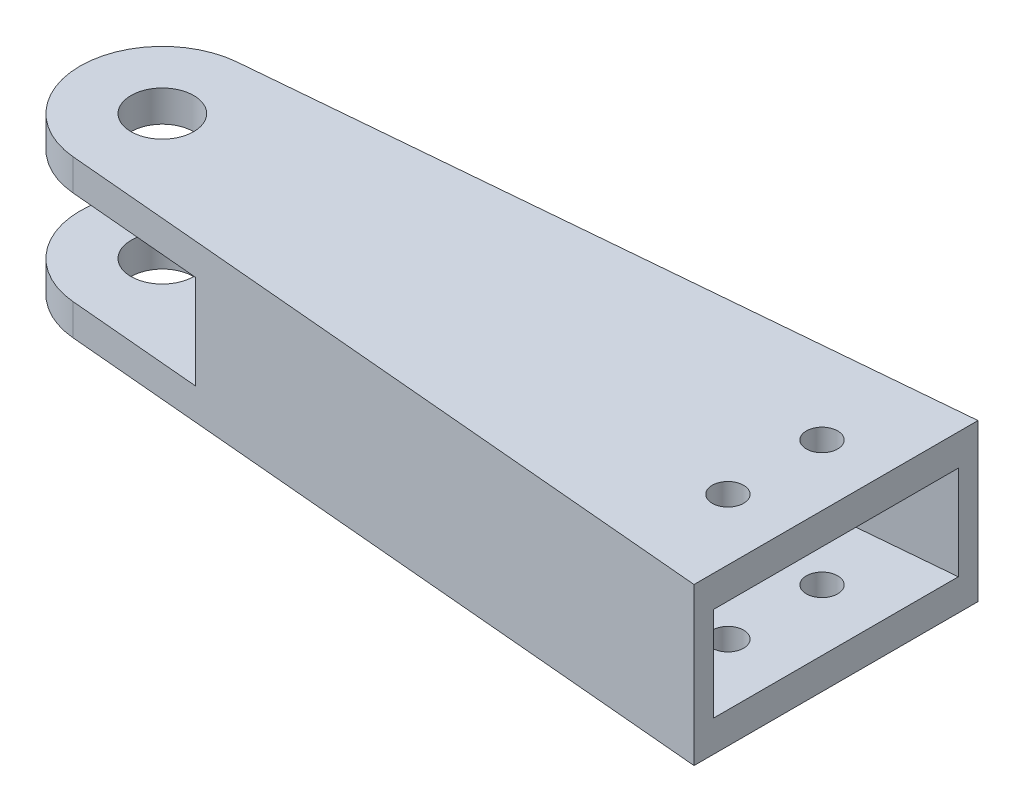
SolidWorks part; units mm, degrees
ref_plane "Front Plane" through (0, 0, 0) normal (0, 0, 1) x (1, 0, 0)
ref_plane "Top Plane" through (0, 0, 0) normal (0, 1, 0) x (1, 0, 0)
ref_plane "Right Plane" through (0, 0, 0) normal (1, 0, 0) x (0, 0, -1)
ref_plane "Plane1" through (0, 20, 0) normal (0, 1, 0) x (1, 0, 0)
sketch "Sketch1" plane through (0, 20, 0) normal (0, 1, 0) x (1, 0, 0)
  line L0 (-75, -18.1061) -> (-75, 18.1061)
  line L1 (-75, 18.1061) -> (-161.8212, 10.4595)
  line L2 (-161.8212, -10.4595) -> (-75, -18.1061)
  arc A0 (-161.8212, 10.4595) -> (-161.8212, -10.4595) centre (-160.9, 0) ccw
extrude "Boss-Extrude1" add sketch "Sketch1" against normal blind 4
sketch "Sketch2" plane through (0, 16, 0) normal (0, -1, 0) x (1, 0, 0)
  line L0 (-75, -18.1061) -> (-144.7301, -11.9648)
  line L1 (-144.7301, -11.9648) -> (-144.5108, -9.4744)
  line L2 (-144.5108, -9.4744) -> (-144.5108, 9.4744)
  line L3 (-144.5108, 9.4744) -> (-144.7301, 11.9648)
  line L4 (-144.7301, 11.9648) -> (-75, 18.1061)
  line L5 (-75, 18.1061) -> (-75, -18.1061)
extrude "Boss-Extrude2" add sketch "Sketch2" along normal blind 12
sketch "Sketch3" plane through (0, 4, 0) normal (0, -1, 0) x (1, 0, 0)
  line L0 (-75, -18.1061) -> (-161.8212, -10.4595)
  line L1 (-161.8212, 10.4595) -> (-75, 18.1061)
  line L2 (-75, 18.1061) -> (-75, -18.1061)
  arc A0 (-161.8212, -10.4595) -> (-161.8212, 10.4595) centre (-160.9, 0) cw
extrude "Boss-Extrude3" add sketch "Sketch3" along normal blind 4
sketch "Sketch4" plane through (-75, 0, 0) normal (1, 0, 0) x (0, 0, -1)
  line L0 (15.5964, 4) -> (15.5964, 16)
  line L1 (15.5964, 16) -> (-15.5964, 16)
  line L2 (-15.5964, 16) -> (-15.5964, 4)
  line L3 (-15.5964, 4) -> (15.5964, 4)
extrude "Cut-Extrude1" cut sketch "Sketch4" against normal blind 20
draft "Draft1" type of draft neutral plane draft angle 5.033 faces to draft 2 face at (-85, 10, 15.5964) face at (-85, 10, -15.5964) neutral plane through (-75, 16, 18.1061) neutral plane normal (1, 0, 0) parameters "D1"=5.033
hole_wizard "Ø4.0 (4) Diameter Hole1" positions "Sketch6" profile "Sketch5" hole size "Ø4.0" standard "ANSI Metric"
sketch "Sketch6" plane through (0, 4, 0) normal (0, 1, 0) x (1, 0, 0)
  point P0 (-82.8, 6.0176)
  point P1 (-82.8, -5.9824)
sketch "Sketch5" plane through (-82.8, 4, -6.0176) normal (1, 0, 0) x (0, 0, 1)
  line L0 (0, 0) -> (0, 4)
  line L1 (0, 4) -> (2, 4)
  line L2 (2, 4) -> (2, 0)
  line L5 (2, 0) -> (0, 0)
  line L11 (0, -6.35) -> (0, 107.95) construction
  dimension "Thru Hole Dia." = 4
  dimension "Thru Hole Depth" = 4
hole_wizard "Ø4.0 (4) Diameter Hole2" positions "Sketch8" profile "Sketch7" hole size "Ø4.0" standard "ANSI Metric"
sketch "Sketch8" plane through (0, 20, 0) normal (0, 1, 0) x (1, 0, 0)
  point P0 (-82.8, 6.0176)
  point P1 (-82.8, -5.9824)
sketch "Sketch7" plane through (-82.8, 20, -6.0176) normal (1, 0, 0) x (0, 0, 1)
  line L0 (0, 0) -> (0, 20)
  line L1 (0, 20) -> (2, 20)
  line L2 (2, 20) -> (2, 0)
  line L5 (2, 0) -> (0, 0)
  line L11 (0, -6.35) -> (0, 107.95) construction
  dimension "Thru Hole Dia." = 4
  dimension "Thru Hole Depth" = 20
hole_wizard "Ø8.0 (8) Diameter Hole1" positions "Sketch10" profile "Sketch9" hole size "Ø8.0" standard "ANSI Metric"
sketch "Sketch10" plane through (0, 20, 0) normal (0, 1, 0) x (1, 0, 0)
  point P0 (-160.9, 0)
sketch "Sketch9" plane through (-160.9, 20, 0) normal (1, 0, 0) x (0, 0, 1)
  line L0 (0, 0) -> (0, 4)
  line L1 (0, 4) -> (4, 4)
  line L2 (4, 4) -> (4, 0)
  line L5 (4, 0) -> (0, 0)
  line L11 (0, -6.35) -> (0, 107.95) construction
  dimension "Thru Hole Dia." = 8
  dimension "Thru Hole Depth" = 4
hole_wizard "Ø8.0 (8) Diameter Hole2" positions "Sketch12" profile "Sketch11" hole size "Ø8.0" standard "ANSI Metric"
sketch "Sketch12" plane through (0, 4, 0) normal (0, 1, 0) x (1, 0, 0)
  point P0 (-160.9, 0)
sketch "Sketch11" plane through (-160.9, 4, 0) normal (1, 0, 0) x (0, 0, 1)
  line L0 (0, 0) -> (0, 4)
  line L1 (0, 4) -> (4, 4)
  line L2 (4, 4) -> (4, 0)
  line L5 (4, 0) -> (0, 0)
  line L11 (0, -6.35) -> (0, 107.95) construction
  dimension "Thru Hole Dia." = 8
  dimension "Thru Hole Depth" = 4
